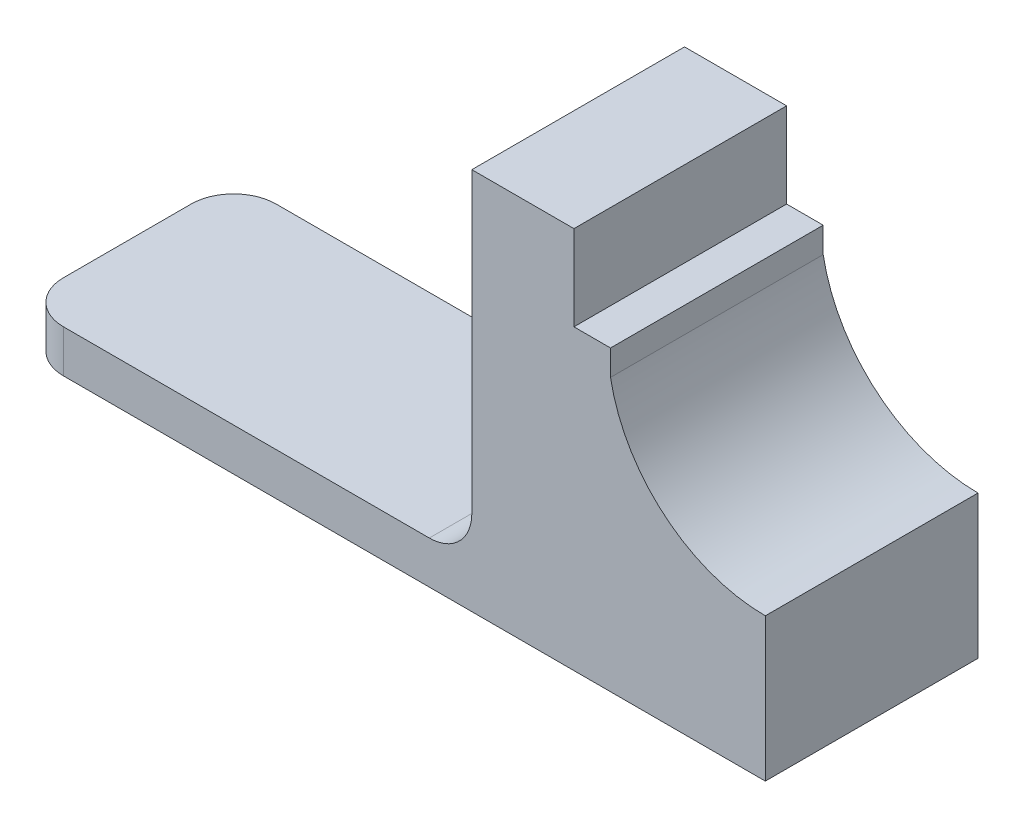
SolidWorks part; units mm, degrees
ref_plane "Front Plane" through (0, 0, 0) normal (0, 0, 1) x (1, 0, 0)
ref_plane "Top Plane" through (0, 0, 0) normal (0, 1, 0) x (1, 0, 0)
ref_plane "Right Plane" through (0, 0, 0) normal (1, 0, 0) x (0, 0, -1)
sketch "Sketch3" plane through (0, 0, 0) normal (0, 0, 1) x (1, 0, 0)
  line L0 (-2079.2127, -769.8632) -> (-860.0127, -769.8632)
  line L1 (-733.0127, 246.1368) -> (-428.1506, 246.1368)
  line L2 (-2079.2127, -769.8632) -> (-2079.2127, -896.8632)
  line L3 (-2079.2127, -896.8632) -> (143.2873, -896.8632)
  line L4 (143.2873, -469.3379) -> (143.2873, -896.8632)
  line L5 (-733.0127, -642.8632) -> (-733.0127, 246.1368)
  line L6 (-428.1506, 246.1368) -> (-428.1506, -7.8632)
  line L7 (-428.1506, -7.8632) -> (-326.6127, -7.8632)
  line L8 (-318.9297, -84.0632) -> (-318.9297, -7.8632)
  line L9 (-318.9297, -7.8632) -> (-326.6127, -7.8632)
  arc A0 (-860.0127, -769.8632) -> (-733.0127, -642.8632) centre (-860.0127, -642.8632) ccw
  arc A1 (-318.9297, -84.0632) -> (143.2873, -469.3379) centre (143.2873, 0.5621) ccw
  point P9 (-733.0127, -769.8632)
  dimension "D5" = 127
  dimension "D7" = 939.8
  dimension "D1" = 2222.5
  dimension "D2" = 1143
  dimension "D3" = 1346.2
  dimension "D4" = 127
  dimension "D6" = 571.5
  dimension "D8" = 254
  dimension "D9" = 76.2
extrude "Boss-Extrude1" add sketch "Sketch3" along normal blind 635
fillet "Fillet5" radius 127 1 edges at (-2079.2127, -833.3632, 635)
fillet "Fillet6" radius 127 1 edges at (-2079.2127, -833.3632, 0)
